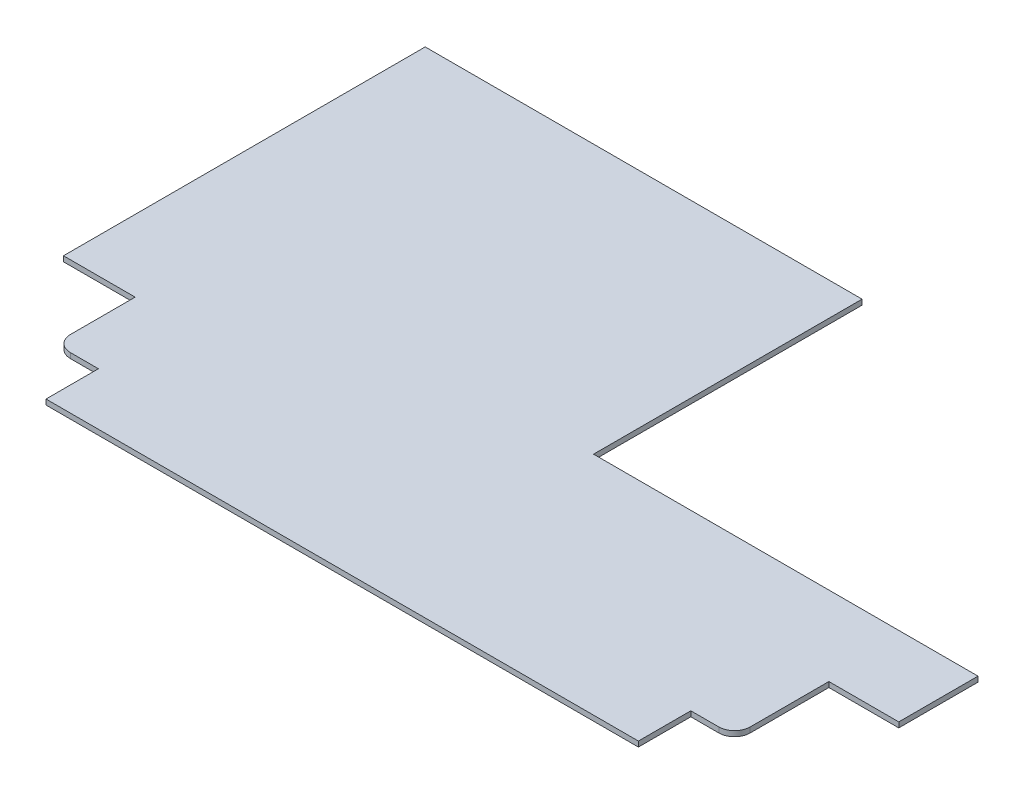
SolidWorks part; units mm, degrees
ref_plane "Alzado" through (0, 0, 0) normal (0, 0, 1) x (1, 0, 0)
ref_plane "Planta" through (0, 0, 0) normal (0, 1, 0) x (1, 0, 0)
ref_plane "Vista lateral" through (0, 0, 0) normal (1, 0, 0) x (0, 0, -1)
sketch "Croquis1" plane through (0, 0, 0) normal (0, 1, 0) x (1, 0, 0)
  line L1 (-125, 125) -> (125, 125)
  line L2 (-125, 125) -> (-125, -125)
  line L3 (-125, -125) -> (125, -125)
  line L4 (125, 125) -> (125, -125)
  line L5 (-125, 125) -> (125, -125) construction
  line L6 (-125, -125) -> (125, 125) construction
  point P0 (0, 0)
extrude "Saliente-Extruir1" add sketch "Croquis1" along normal blind 3
sketch "Croquis2" plane through (0, 3, 0) normal (0, 1, 0) x (1, 0, 0)
  line L0 (125, -125) -> (125, 125) construction
  line L1 (-125, 125) -> (125, 125)
  line L2 (-125, 125) -> (-125, 128)
  line L3 (-125, 128) -> (125, 128)
  line L4 (125, 125) -> (125, 128)
extrude "Saliente-Extruir2" add sketch "Croquis2" against normal blind 3
sketch "Croquis3" plane through (0, 3, 0) normal (0, 1, 0) x (1, 0, 0)
  line L1 (125, -125) -> (345, -125)
  line L2 (125, -125) -> (125, -25.66)
  line L3 (125, -25.66) -> (345, -25.66)
  line L4 (345, -125) -> (345, -25.66)
  dimension "D1" = 220
  dimension "D2" = 99.34
extrude "Saliente-Extruir4" add sketch "Croquis3" against normal blind 3
sketch "Croquis4" plane through (0, 3, 0) normal (0, 1, 0) x (1, 0, 0)
  line L1 (-125, -125) -> (-84, -125)
  line L2 (-125, -125) -> (-125, -73)
  line L3 (-125, -73) -> (-84, -73)
  line L4 (-84, -125) -> (-84, -73)
  dimension "D1" = 41
  dimension "D2" = 52
extrude "Cortar-Extruir1" cut sketch "Croquis4" against normal blind 3
sketch "Croquis5" plane through (0, 3, 0) normal (0, 1, 0) x (1, 0, 0)
  line L0 (-84, -125) -> (-75, -125) construction
  line L1 (-84, -125) -> (345, -125) construction
  line L2 (-75, -125) -> (-75, -116) construction
  line L3 (-84, -125) -> (-84, -73) construction
  line L4 (-84, -116) -> (-84, -125)
  line L5 (-84, -125) -> (-75, -125)
  arc A0 (-75, -125) -> (-84, -116) centre (-75, -116) cw
extrude "Cortar-Extruir2" cut sketch "Croquis5" against normal blind 3
sketch "Croquis6" plane through (0, 3, 0) normal (0, 1, 0) x (1, 0, 0)
  line L0 (-75, -125) -> (345, -125) construction
  line L1 (-59, -125) -> (280, -125)
  line L2 (-59, -125) -> (-59, -155)
  line L3 (-59, -155) -> (280, -155)
  line L4 (280, -125) -> (280, -155)
  line L5 (-125, 128) -> (-125, -73) construction
  line L6 (345, -125) -> (345, -25.66) construction
  dimension "D1" = 66
  dimension "D2" = 65
extrude "Saliente-Extruir5" add sketch "Croquis6" against normal blind 3
sketch "Croquis7" plane through (0, 3, 0) normal (0, 1, 0) x (1, 0, 0)
  line L0 (345, -72) -> (304, -72)
  line L1 (345, -125) -> (345, -25.66) construction
  line L2 (304, -125) -> (304, -116) construction
  line L3 (280, -125) -> (345, -125) construction
  line L4 (304, -116) -> (295, -116) construction
  line L5 (304, -116) -> (304, -72)
  line L6 (295, -125) -> (345, -125)
  line L7 (345, -125) -> (345, -72)
  line L8 (-59, -155) -> (280, -155) construction
  arc A0 (304, -116) -> (295, -125) centre (295, -116) cw
  dimension "D1" = 83
extrude "Cortar-Extruir3" cut sketch "Croquis7" against normal blind 3
sketch "Croquis8" plane through (0, 3, 0) normal (0, 1, 0) x (1, 0, 0)
  line L1 (304, -72) -> (305, -72)
  line L2 (304, -72) -> (304, -116)
  line L3 (304, -116) -> (305, -116)
  line L4 (305, -72) -> (305, -116)
extrude "Saliente-Extruir6" add sketch "Croquis8" against normal blind 3
sketch "Croquis9" plane through (0, 3, 0) normal (0, 1, 0) x (1, 0, 0)
  line L0 (345, -72) -> (345, -178.0353) construction
  line L1 (305, -116) -> (296, -116) construction
  line L2 (295, -125) -> (296, -125)
  line L3 (295, -125) -> (304, -116)
  line L4 (304, -116) -> (305, -116)
  arc A0 (305, -116) -> (296, -125) centre (296, -116) cw
  arc A1 (295, -125) -> (304, -116) centre (295, -116) ccw construction
extrude "Saliente-Extruir7" add sketch "Croquis9" against normal blind 3
sketch "Croquis10" plane through (0, 3, 0) normal (0, 1, 0) x (1, 0, 0)
  line L0 (-59, -155) -> (-166.212, -155) construction
  line L1 (-84, -116) -> (-84, -73) construction
  line L2 (-125, -73) -> (-84, -73)
  line L3 (-125, -73) -> (-125, -79)
  line L4 (-125, -79) -> (-84, -79)
  line L5 (-84, -73) -> (-84, -79)
  dimension "D1" = 76
extrude "Saliente-Extruir9" add sketch "Croquis10" against normal blind 3
sketch "Croquis11" plane through (0, 3, 0) normal (0, 1, 0) x (1, 0, 0)
  line L0 (345, -72) -> (345, -25.66) construction
  line L1 (305, -72) -> (345, -72)
  line L2 (305, -72) -> (305, -71)
  line L3 (305, -71) -> (345, -71)
  line L4 (345, -72) -> (345, -71)
extrude "Cortar-Extruir4" cut sketch "Croquis11" against normal blind 3
